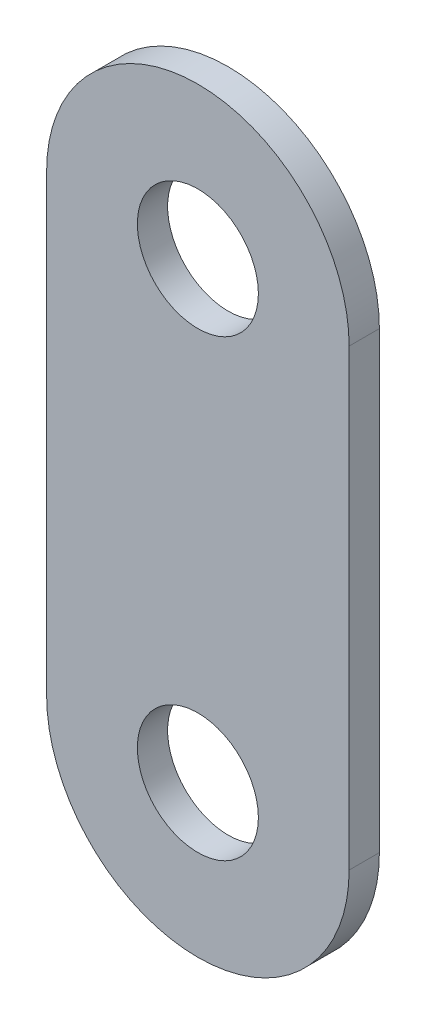
SolidWorks part; units mm, degrees
material "AISI 1020 Steel, Cold Rolled"
ref_plane "Front Plane" through (0, 0, 0) normal (0, 0, 1) x (1, 0, 0)
ref_plane "Top Plane" through (0, 0, 0) normal (0, 1, 0) x (1, 0, 0)
ref_plane "Right Plane" through (0, 0, 0) normal (1, 0, 0) x (0, 0, -1)
sketch "Sketch1" plane through (0, 0, 0) normal (0, 0, 1) x (1, 0, 0)
  line L8 (0, 50) -> (0, 125)
  line L9 (50, 50) -> (50, 125)
  circle A3 centre (25, 50) radius 10
  circle A4 centre (25, 125) radius 10
  arc A5 (0, 50) -> (50, 50) centre (25, 50) ccw
  arc A6 (0, 125) -> (50, 125) centre (25, 125) cw
extrude "Boss-Extrude1" add sketch "Sketch1" along normal blind 5
sketch "Sketch2" [suppressed] plane through (0, 0, 5) normal (0, 0, 1) x (1, 0, 0)
  line L0 (25, 125) -> (108.8789, 0.6444)
  line L1 (25, 50) -> (-99.3556, -33.8789)
  line L2 (25, 50) -> (-58.8789, 174.3556)
  line L3 (25, 125) -> (149.3556, 208.8789)
